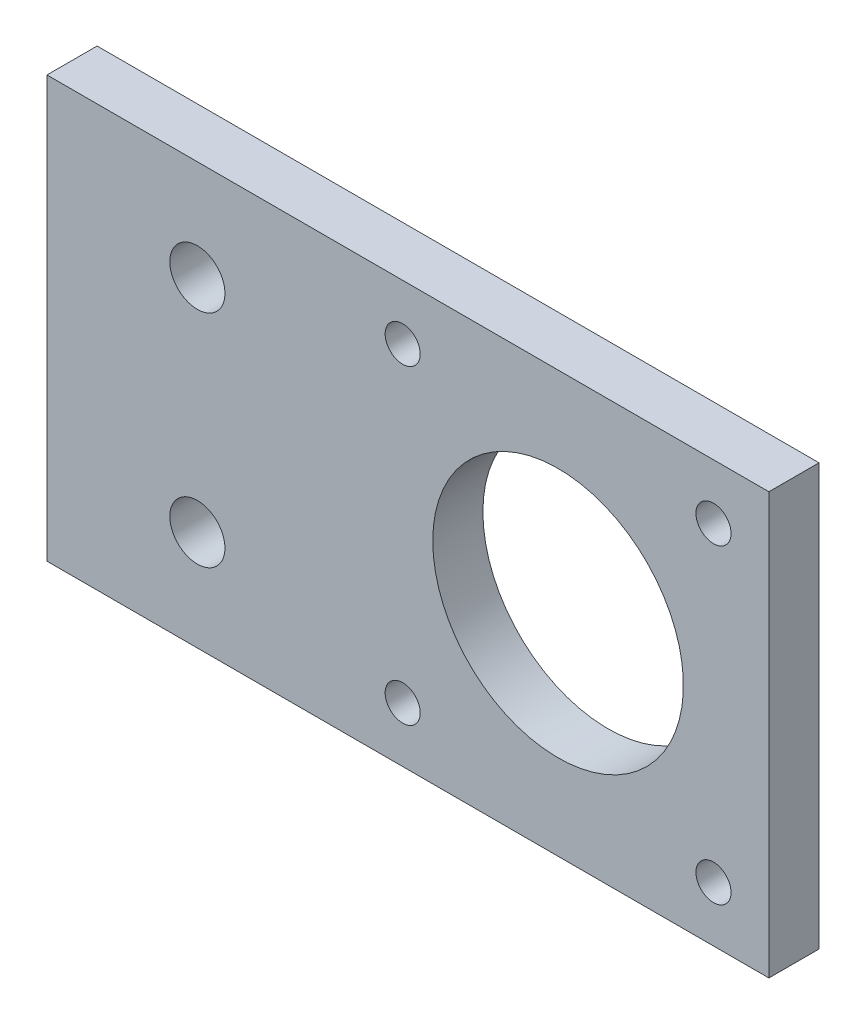
SolidWorks part; units mm, degrees
ref_plane "Plan de face" through (0, 0, 0) normal (0, 0, 1) x (1, 0, 0)
ref_plane "Plan de dessus" through (0, 0, 0) normal (0, 1, 0) x (1, 0, 0)
ref_plane "Plan de droite" through (0, 0, 0) normal (1, 0, 0) x (0, 0, -1)
sketch "Sketch1" plane through (0, 0, 0) normal (0, 0, 1) x (1, 0, 0)
  line L1 (36, -21) -> (-36, -21)
  line L2 (36, -21) -> (36, 21)
  line L3 (36, 21) -> (-36, 21)
  line L4 (-36, -21) -> (-36, 21)
  line L5 (36, -21) -> (-36, 21) construction
  line L6 (36, 21) -> (-36, -21) construction
  point P0 (0, 0)
  dimension "D1" = 72
  dimension "D2" = 42
extrude "Boss-Extrude1" add sketch "Sketch1" along normal blind 5
sketch "Sketch2" plane through (0, 0, 5) normal (0, 0, 1) x (1, 0, 0)
  circle A0 centre (30.475, 15.5) radius 1.75
  circle A1 centre (30.475, -15.5) radius 1.75
  circle A2 centre (-0.525, -15.5) radius 1.75
  circle A3 centre (-0.525, 15.5) radius 1.75
extrude "Cut-Extrude1" cut sketch "Sketch2" against normal blind 10
hole_wizard "Dégagement M51" positions "Sketch4" profile "Sketch5" hole size "M5" standard "ISO" end condition through all
sketch "Sketch4" plane through (0, 0, 0) normal (0, 0, -1) x (-1, 0, 0)
  line L0 (36, 21) -> (36, -21) construction
  line L1 (-36, 21) -> (36, 21) construction
  line L2 (36, -21) -> (-36, -21) construction
  point P0 (21, 11)
  point P2 (21, -11)
  dimension "D1" = 15
  dimension "D2" = 10
  dimension "D3" = 10
  dimension "D4" = 15
sketch "Sketch5" plane through (-21, 11, 0) normal (1, 0, 0) x (0, 1, 0)
  line L0 (0, 0) -> (0, 5)
  line L1 (0, 5) -> (2.75, 5)
  line L2 (2.75, 5) -> (2.75, 0)
  line L5 (2.75, 0) -> (0, 0)
  line L11 (0, -6.35) -> (0, 107.95) construction
  dimension "Diamètre du perçage jusqu'au prochain" = 5.5
  dimension "Profondeur du perçage jusqu'au prochain" = 5
sketch "Sketch6" plane through (0, 0, 0) normal (0, 0, -1) x (-1, 0, 0)
  circle A0 centre (-14.975, 0) radius 12.5
  dimension "D1" = 25
extrude "Cut-Extrude2" cut sketch "Sketch6" against normal through all
